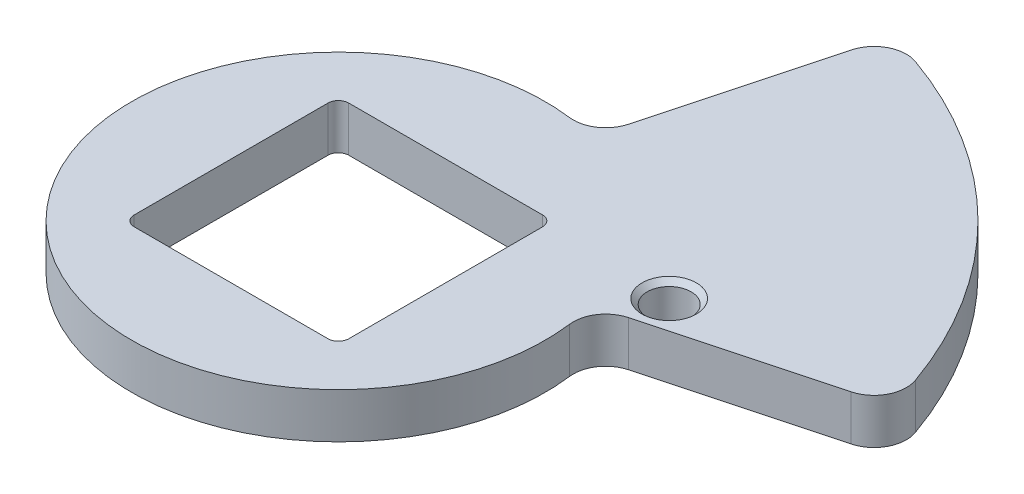
SolidWorks part; units mm, degrees
ref_plane "Alzado" through (0, 0, 0) normal (0, 0, 1) x (1, 0, 0)
ref_plane "Planta" through (0, 0, 0) normal (0, 1, 0) x (1, 0, 0)
ref_plane "Vista lateral" through (0, 0, 0) normal (1, 0, 0) x (0, 0, -1)
sketch "Croquis1" plane through (0, 0, 0) normal (0, 1, 0) x (1, 0, 0)
  line L0 (0, 0) -> (20.32, 0) construction
  line L1 (0, 0) -> (34.3877, 34.3877) construction
  line L2 (11.5045, 42.9354) -> (5.2592, 19.6276)
  line L3 (42.9354, 11.5045) -> (19.6276, 5.2592)
  line L4 (19.6276, 5.2592) -> (0, 0) construction
  line L6 (-10.541, -10.541) -> (10.541, -10.541)
  line L7 (-10.541, -10.541) -> (-10.541, 10.541)
  line L8 (-10.541, 10.541) -> (10.541, 10.541)
  line L9 (10.541, -10.541) -> (10.541, 10.541)
  line L10 (-10.541, -10.541) -> (10.541, 10.541) construction
  line L11 (-10.541, 10.541) -> (10.541, -10.541) construction
  arc A0 (5.2592, 19.6276) -> (19.6276, 5.2592) centre (0, 0) ccw
  arc A1 (11.5045, 42.9354) -> (42.9354, 11.5045) centre (0, 0) cw
  circle A2 centre (22.86, 9.652) radius 2.159
  dimension "D1" = 40.64
  dimension "D4" = 44.45
  dimension "D6" = 4.318
  dimension "D2" = 45
  dimension "D3" = 15
  dimension "D5" = 21.082
  dimension "D7" = 9.652
  dimension "D8" = 22.86
extrude "Saliente-Extruir1" add sketch "Croquis1" along normal blind 4.445
fillet "Redondeo1" radius 3.175 4 edges at (11.5045, 2.2225, -42.9354) (42.9354, 2.2225, -11.5045) (5.2592, 2.2225, -19.6276) (19.6276, 2.2225, -5.2592)
fillet "Redondeo2" radius 1.016 4 edges at (10.541, 2.2225, -10.541) (10.541, 2.2225, 10.541) (-10.541, 2.2225, 10.541) (-10.541, 2.2225, -10.541)
chamfer "Chaflán1" distance 0.508 angle 45 2 edges at (22.86, 0, -7.493) (22.86, 4.445, -7.493)
